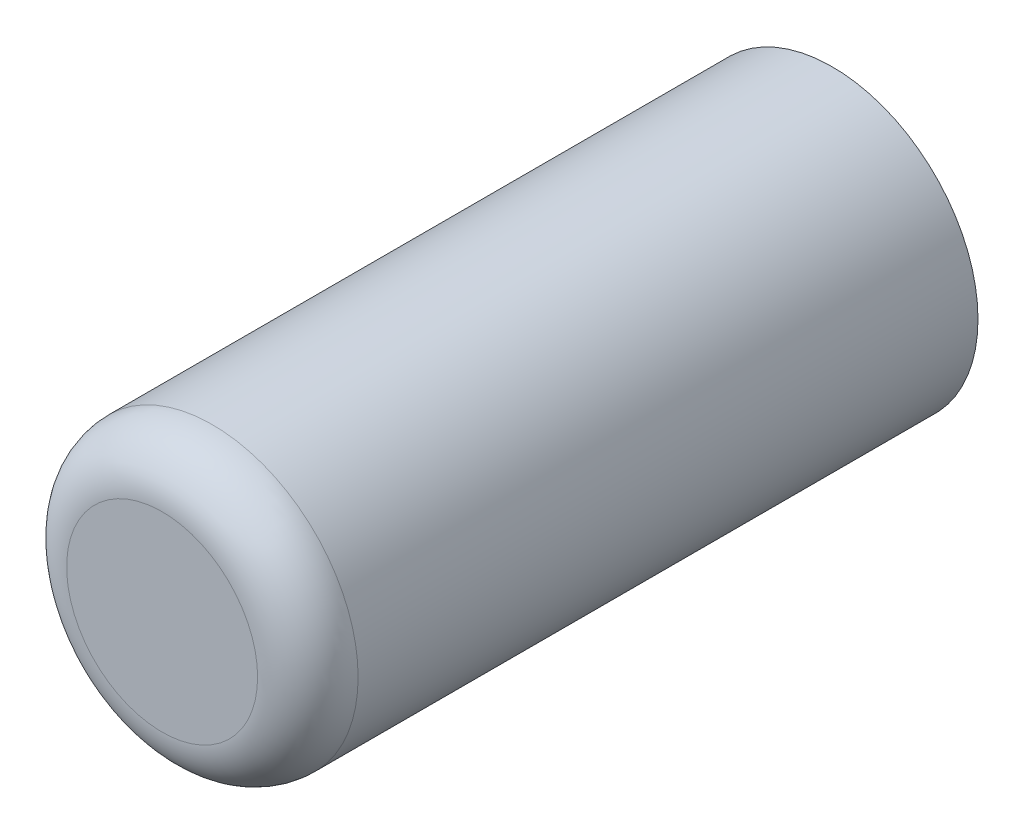
SolidWorks part; units mm, degrees
ref_plane "Front Plane" through (0, 0, 0) normal (1, 0, 0) x (0, 1, 0)
ref_plane "Top Plane" through (0, 0, 0) normal (0, 0, 1) x (0, 1, 0)
ref_plane "Right Plane" through (0, 0, 0) normal (0, 1, 0) x (-1, 0, 0)
sketch "Sketch2" plane through (0, 0, 0) normal (0, 0, 1) x (0, 1, 0)
  circle A0 centre (0, 0) radius 29
  dimension "D1" = 58
extrude "Boss-Extrude1" add sketch "Sketch2" along normal blind 133.35
fillet "Fillet1" radius 10 1 edges at (29, 0, 133.35)
shell "Shell1" thickness 1
